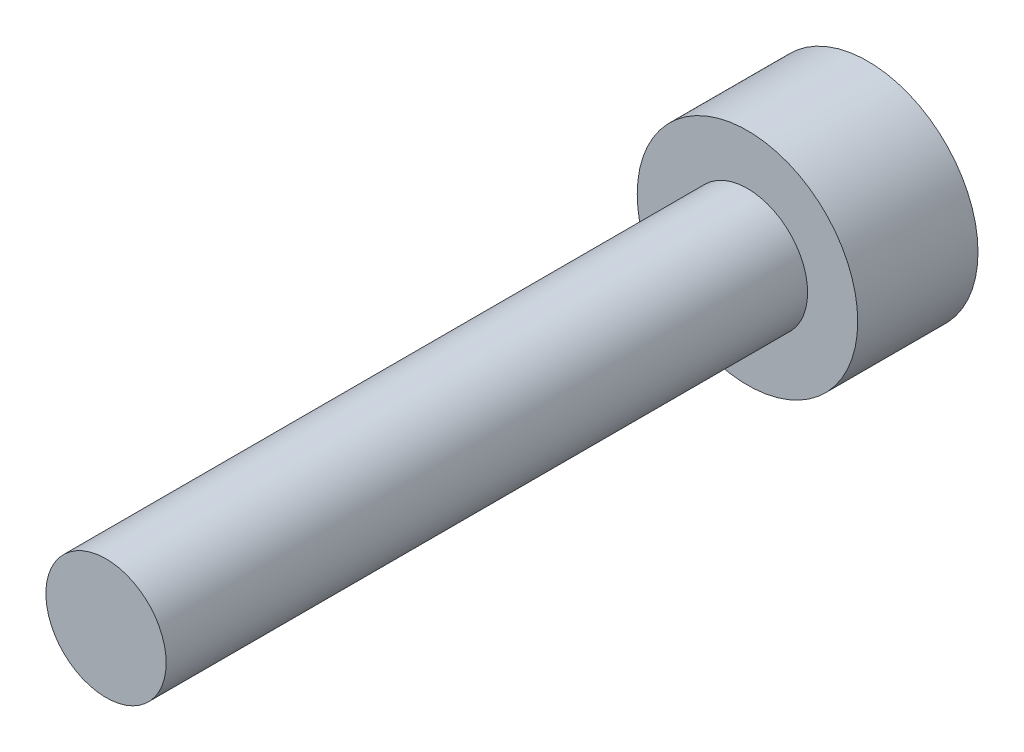
SolidWorks part; units mm, degrees
material "AISI 4340 Steel, normalized"
ref_plane "Front Plane" through (0, 0, 0) normal (0, 0, 1) x (1, 0, 0)
ref_plane "Top Plane" through (0, 0, 0) normal (0, 1, 0) x (1, 0, 0)
ref_plane "Right Plane" through (0, 0, 0) normal (1, 0, 0) x (0, 0, -1)
sketch "Sketch1" plane through (0, 0, 0) normal (0, 0, 1) x (1, 0, 0)
  circle A0 centre (0, 0) radius 2.75
extrude "Head_Envelope" add sketch "Sketch1" along normal blind 3 from offset 3
sketch "Sketch2" plane through (0, 0, 0) normal (0, 0, 1) x (1, 0, 0)
  circle A0 centre (0, 0) radius 1.5
extrude "Thread_Major_Envelope" add sketch "Sketch2" along normal blind 16
